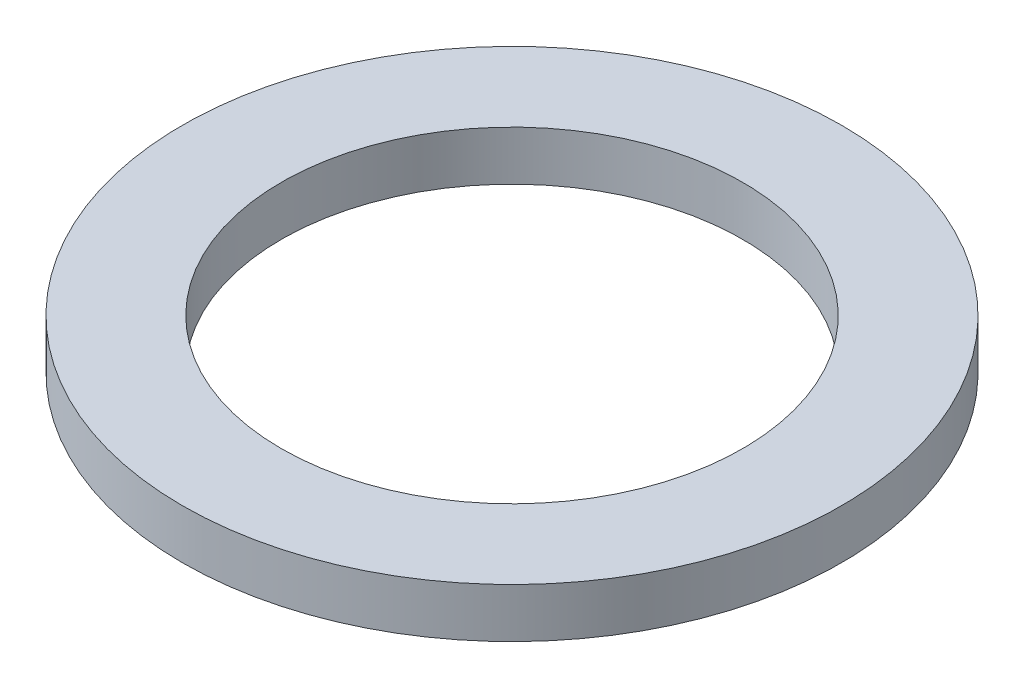
SolidWorks part; units mm, degrees
ref_plane "Plane1" through (0, 0, 0) normal (0, 0, 1) x (1, 0, 0)
ref_plane "Plane2" through (0, 0, 0) normal (0, 1, 0) x (1, 0, 0)
ref_plane "Plane3" through (0, 0, 0) normal (1, 0, 0) x (0, 0, -1)
revolve "Base-Revolve" add sketch "Sketch1" angle 360 about L0
sketch "Sketch1" plane through (0, 0, 0) normal (0, 0, 1) x (1, 0, 0)
  line L0 (0, 10.2161) -> (0, -9.1945) construction
  line L1 (0, 0) -> (7, 0) construction
  line L2 (0, 0) -> (-7, 0) construction
  line L3 (7, 0) -> (10, 0)
  line L4 (7, 0) -> (7, 1.5)
  line L5 (10, 1.5) -> (7, 1.5)
  line L6 (10, 1.5) -> (10, 0)
  line L7 (0, 0) -> (-10, 0) construction
  line L8 (10, 0) -> (0, 0) construction
  dimension "_d" = 14
  dimension "t" = 1.5
  dimension "_dd" = 20
